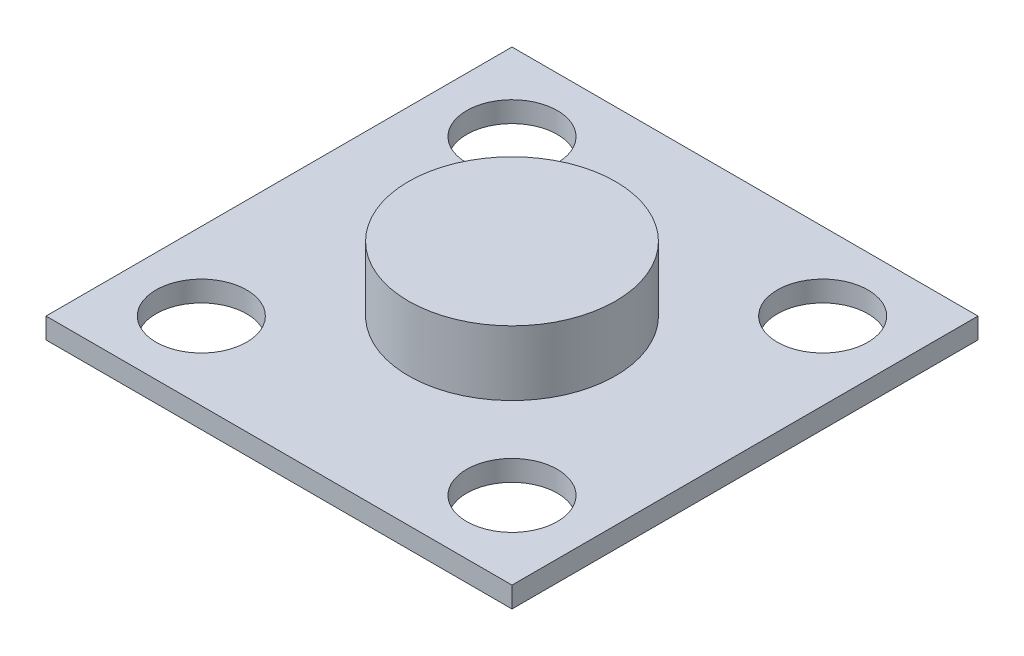
SolidWorks part; units mm, degrees
ref_plane "前视基准面" through (0, 0, 0) normal (0, 0, 1) x (1, 0, 0)
ref_plane "上视基准面" through (0, 0, 0) normal (0, 1, 0) x (1, 0, 0)
ref_plane "右视基准面" through (0, 0, 0) normal (1, 0, 0) x (0, 0, -1)
sketch "草图1" plane through (0, 0, 0) normal (0, 1, 0) x (1, 0, 0)
  line L1 (0, 0) -> (18, 0)
  line L2 (0, 0) -> (0, 18)
  line L3 (0, 18) -> (18, 18)
  line L4 (18, 0) -> (18, 18)
  dimension "D1" = 18
  dimension "D2" = 18
extrude "凸台-拉伸1" add sketch "草图1" along normal blind 0.8
sketch "草图2" plane through (0, 0.8, 0) normal (0, 1, 0) x (1, 0, 0)
  line L0 (9, 18) -> (9, 15) construction
  line L1 (3, 15) -> (15, 15) construction
  line L2 (3, 15) -> (3, 3) construction
  line L3 (3, 3) -> (15, 3) construction
  line L4 (15, 15) -> (15, 3) construction
  line L5 (18, 18) -> (0, 18) construction
  line L6 (0, 9) -> (3, 9) construction
  line L7 (0, 18) -> (0, 0) construction
  circle A0 centre (3, 15) radius 1.75
  circle A1 centre (15, 15) radius 1.75
  circle A2 centre (15, 3) radius 1.75
  circle A3 centre (3, 3) radius 1.75
  dimension "D3" = 3.5
  dimension "D1" = 12
  dimension "D2" = 12
extrude "切除-拉伸1" cut sketch "草图2" against normal through all
sketch "草图3" plane through (0, 0.8, 0) normal (0, 1, 0) x (1, 0, 0)
  line L0 (9, 18) -> (9, -49982) construction
  line L1 (18, 18) -> (0, 18) construction
  line L2 (0, 9) -> (50000, 9) construction
  line L3 (0, 18) -> (0, 0) construction
  circle A0 centre (9, 9) radius 4
  point P4 (9, 18)
  point P9 (0, 9)
  dimension "D1" = 8
extrude "凸台-拉伸2" add sketch "草图3" along normal blind 2.5
